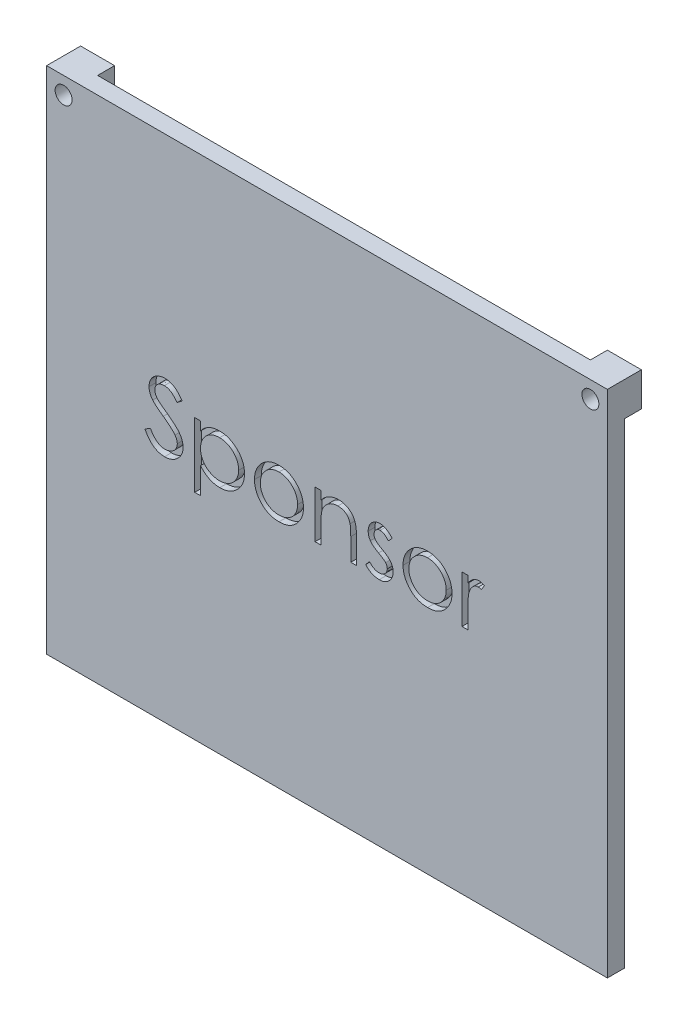
SolidWorks part; units mm, degrees
ref_plane "Plan de face" through (0, 0, 0) normal (0, 0, 1) x (1, 0, 0)
ref_plane "Plan de dessus" through (0, 0, 0) normal (0, 1, 0) x (1, 0, 0)
ref_plane "Plan de droite" through (0, 0, 0) normal (1, 0, 0) x (0, 0, -1)
sketch "Esquisse1" plane through (0, 0, 0) normal (0, 0, 1) x (1, 0, 0)
  line L1 (82.5, 75) -> (-82.5, 75)
  line L2 (82.5, 75) -> (82.5, -75)
  line L3 (82.5, -75) -> (-82.5, -75)
  line L4 (-82.5, 75) -> (-82.5, -75)
  line L5 (82.5, 75) -> (-82.5, -75) construction
  line L6 (82.5, -75) -> (-82.5, 75) construction
  point P0 (0, 0)
  dimension "D1" = 150
  dimension "D2" = 165
extrude "BASE" add sketch "Esquisse1" along normal blind 5
sketch "Esquisse2" plane through (0, 75, 0) normal (0, 1, 0) x (1, 0, 0)
  line L0 (0, 17.2478) -> (0, -23.2394) construction
  line L1 (-82.5, 0) -> (-82.5, 5)
  line L2 (82.5, 0) -> (-82.5, 0) construction
  line L3 (-82.5, 5) -> (-72.5, 5)
  line L4 (-72.5, 5) -> (-72.5, 0)
  line L5 (-82.5, -5) -> (-82.5, 0) construction
  line L6 (-82.5, 0) -> (-72.5, 0)
  line L7 (82.5, 0) -> (82.5, 5)
  line L8 (82.5, 0) -> (72.5, 0)
  line L9 (72.5, 5) -> (72.5, 0)
  line L10 (82.5, 5) -> (72.5, 5)
  dimension "D1" = 5
  dimension "D2" = 10
  dimension "D3" = 0
extrude "BOSS - TIGE" add sketch "Esquisse2" against normal blind 10
sketch "Esquisse3" plane through (0, 0, -5) normal (0, 0, -1) x (-1, 0, 0)
  line L0 (-82.5, 75) -> (-72.5, 65) construction
  line L1 (-72.5, 65) -> (-77.5, 65) construction
  line L2 (-82.5, 65) -> (-72.5, 65) construction
  line L3 (-77.5, 65) -> (-77.5, 75) construction
  line L4 (-82.5, 75) -> (-72.5, 75) construction
  line L5 (0, 61.3494) -> (0, 80.8747) construction
  circle A0 centre (-77.5, 70) radius 2.5
  circle A1 centre (77.5, 70) radius 2.5
  dimension "D1" = 5
extrude "VIDE VIS" cut sketch "Esquisse3" against normal through all
sketch "Esquisse4" plane through (0, 0, 5) normal (0, 0, 1) x (1, 0, 0)
  line L0 (-54.0688, -6.818) -> (69.3121, -6.818) construction
  text T0 "Sponsor" font "Century Gothic" height in points 72
extrude "Enlèv. mat.-Extru.2" cut sketch "Esquisse4" against normal blind 2
